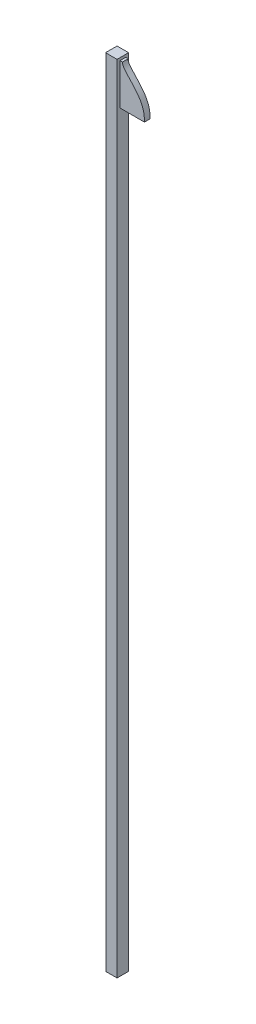
SolidWorks part; units mm, degrees
ref_plane "Front Plane" through (0, 0, 0) normal (0, 0, 1) x (1, 0, 0)
ref_plane "Top Plane" through (0, 0, 0) normal (0, 1, 0) x (1, 0, 0)
ref_plane "Right Plane" through (0, 0, 0) normal (1, 0, 0) x (0, 0, -1)
ref_plane "Plane1" through (0, 0, -0.1102) normal (0, 0, -1) x (-1, 0, 0)
sketch "Sketch1" plane through (0, 0, -0.1102) normal (0, 0, -1) x (-1, 0, 0)
  line L0 (-0.1009, 1.3) -> (0.85, 1.3)
  line L1 (0.85, 1.3) -> (0.85, 2.9)
  line L2 (0.85, 2.9) -> (0.7543, 2.9)
  spline S0 degree 5 poles (0.7543, 2.9) (0.7561, 2.8908) (0.7577, 2.8716) (0.7543, 2.8401) (0.738, 2.7928) (0.6978, 2.7245) (0.6383, 2.647) (0.5611, 2.5601) (0.4699, 2.4641) (0.3702, 2.3595) (0.2684, 2.2472) (0.171, 2.1278) (0.0838, 2.0023) (0.0112, 1.8713) (-0.0446, 1.7352) (-0.0827, 1.5947) (-0.0988, 1.4789) (-0.1029, 1.3901) (-0.1022, 1.3302) (-0.1009, 1.3) knots 0 0 0 0 0 0 0.066667 0.133333 0.2 0.266667 0.333333 0.4 0.466667 0.533333 0.6 0.666667 0.733333 0.8 0.866667 0.933333 1 1 1 1 1 1
extrude "Boss-Extrude1" add sketch "Sketch1" against normal blind 0.2203
ref_plane "Plane2" through (-0.85, 0, 0) normal (1, 0, 0) x (0, 0, -1)
sketch "Sketch2" plane through (-0.85, 0, 0) normal (1, 0, 0) x (0, 0, -1)
  line L0 (0.1102, 3) -> (-0.225, 3)
  line L1 (-0.225, 3) -> (-0.225, -28)
  line L2 (-0.225, -28) -> (0.1102, -28)
  line L3 (0.1102, -28) -> (0.1102, 3)
extrude "Boss-Extrude2" add sketch "Sketch2" against normal blind 0.45
sketch "Sketch3" plane through (0, 0, -0.1102) normal (0, 0, -1) x (-1, 0, 0)
  line L0 (1.3, -28) -> (0.85, -28)
  line L1 (0.85, -28) -> (0.85, 3)
  line L2 (0.85, 3) -> (1.3, 3)
  line L3 (1.3, 3) -> (1.3, -28)
extrude "Boss-Extrude3" add sketch "Sketch3" along normal blind 0.1148
fillet "Fillet1" radius 0.025 1 edges at (-1.3, -12.5, 0.225)
